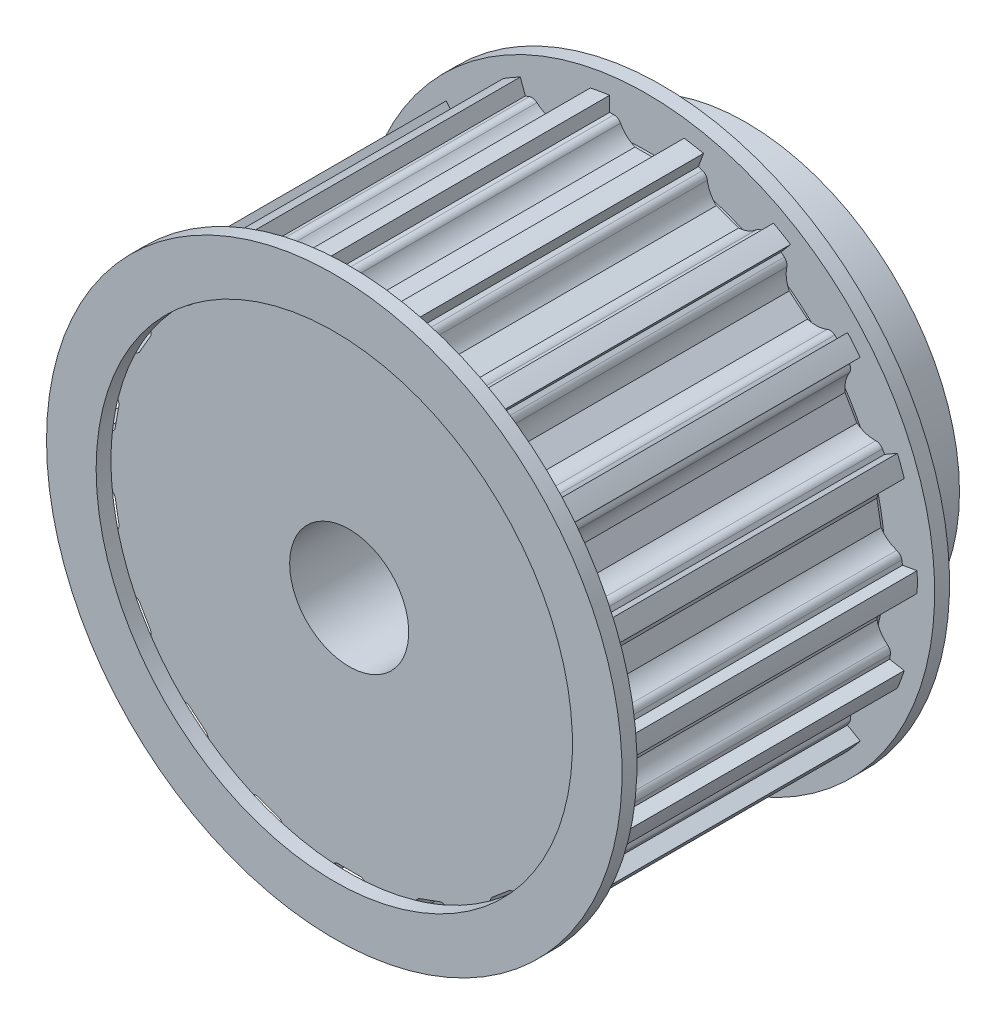
SolidWorks part; units mm, degrees
ref_plane "Front Plane" through (0, 0, 0) normal (0, 0, 1) x (1, 0, 0)
ref_plane "Top Plane" through (0, 0, 0) normal (0, 1, 0) x (1, 0, 0)
ref_plane "Right Plane" through (0, 0, 0) normal (1, 0, 0) x (0, 0, -1)
ref_axis "Axis1" through (0, 0, -88.99) along (0, 0, 1)
sketch "Sketch1" plane through (0, 0, 0) normal (1, 0, 0) x (0, 0, -1)
  line L0 (0, 6) -> (0, 27.25)
  line L1 (0, 27.25) -> (30, 27.25)
  line L2 (30, 27.25) -> (30, 21.5)
  line L3 (30, 21.5) -> (40, 21.5)
  line L4 (40, 21.5) -> (40, 6)
  line L5 (40, 6) -> (0, 6)
  line L6 (88.99, 0) -> (-88.99, 0) construction
  dimension "D1" = 21.25
  dimension "D2" = 30
  dimension "D3" = 10
  dimension "D4" = 15.5
  dimension "D5" = 6
revolve "Revolve1" add sketch "Sketch1" angle 360 about axis through (0, 0, -88.99) along (0, 0, 1)
sketch "Sketch2" plane through (0, 0, 0) normal (0, 0, 1) x (1, 0, 0)
  line L0 (3.3166, 25.5) -> (3.75, 25.5)
  line L1 (-3.75, 27.5) -> (3.75, 27.5)
  line L2 (-3.75, 27.5) -> (-3.75, 25.5)
  line L3 (-3.75, 25.5) -> (-3.3166, 25.5)
  line L4 (3.75, 27.5) -> (3.75, 25.5)
  line L5 (-3.75, 27.5) -> (3.75, 25.5) construction
  line L6 (-3.75, 25.5) -> (3.75, 27.5) construction
  line L7 (-1.199, 23.75) -> (1.199, 23.75)
  arc A0 (-2.6533, 25.1) -> (-1.199, 23.75) centre (0, 26.5) ccw
  arc A1 (3.3166, 25.5) -> (2.6533, 25.1) centre (3.3166, 24.75) ccw
  arc A2 (-2.6533, 25.1) -> (-3.3166, 25.5) centre (-3.3166, 24.75) ccw
  arc A3 (1.199, 23.75) -> (2.6533, 25.1) centre (0, 26.5) ccw
  point P7 (0, 26.5)
  point P11 (2.8284, 25.5)
  dimension "D3" = 3
  dimension "D5" = 0.75
  dimension "D1" = 2
  dimension "D2" = 7.5
  dimension "D4" = 26.5
  dimension "D6" = 2.75
extrude "Cut-Extrude1" cut sketch "Sketch2" against normal through all
pattern_circular "CirPattern1" count 18 over 360 about axis through (0, 0, 0) along (0, 0, 1) of "Cut-Extrude1"
sketch "Sketch3" plane through (0, 0, 0) normal (1, 0, 0) x (0, 0, -1)
  line L1 (-1.5, 29) -> (0, 29)
  line L2 (-1.5, 29) -> (-1.5, 24)
  line L3 (-1.5, 24) -> (0, 24)
  line L4 (0, 29) -> (0, 24)
  line L5 (-1.5, 29) -> (0, 24) construction
  line L6 (-1.5, 24) -> (0, 29) construction
  line L7 (0, 29) -> (-1.4489, 28.6118) construction
  line L8 (0, 29) -> (-0.6431, 31.4)
  line L9 (-1.4489, 28.6118) -> (-2.092, 31.0118)
  line L10 (-0.6431, 31.4) -> (-2.092, 31.0118)
  line L11 (0, 29) -> (-2.092, 31.0118) construction
  line L12 (-1.4489, 28.6118) -> (-0.6431, 31.4) construction
  line L13 (88.99, 0) -> (-88.99, 0) construction
  line L14 (15, -2.9434) -> (15, 38.8724) construction
  line L15 (30, -2.9434) -> (0, -2.9434) construction
  line L16 (31.4489, 28.6118) -> (30.6431, 31.4) construction
  line L17 (30, 29) -> (32.092, 31.0118) construction
  line L18 (30, 29) -> (31.4489, 28.6118) construction
  line L19 (31.5, 24) -> (30, 29) construction
  line L20 (31.5, 29) -> (30, 24) construction
  line L21 (30.6431, 31.4) -> (32.092, 31.0118)
  line L22 (31.4489, 28.6118) -> (32.092, 31.0118)
  line L23 (30, 29) -> (30.6431, 31.4)
  line L24 (30, 29) -> (30, 24)
  line L25 (31.5, 24) -> (30, 24)
  line L26 (31.5, 29) -> (31.5, 24)
  line L27 (31.5, 29) -> (30, 29)
  line L28 (0, 20.9332) -> (0, 18.9642) construction
  point P4 (0, 0)
  point P5 (0, 0)
  point P12 (-1.046, 30.0059)
  point P24 (31.046, 30.0059)
  point P25 (30.28, 25)
  point P26 (-11.0306, 29.2551)
  point P27 (-7.1042, 27.7521)
  point P28 (0, 0)
  point P30 (-17.3736, -13.3092)
  dimension "D1" = 1.5
  dimension "D2" = 5
  dimension "D3" = 1.5
  dimension "D4" = 165
  dimension "D5" = 2.4
  dimension "D6" = 24
revolve "Revolve2" add sketch "Sketch3" angle 360 about axis through (0, 0, -88.99) along (0, 0, 1)
